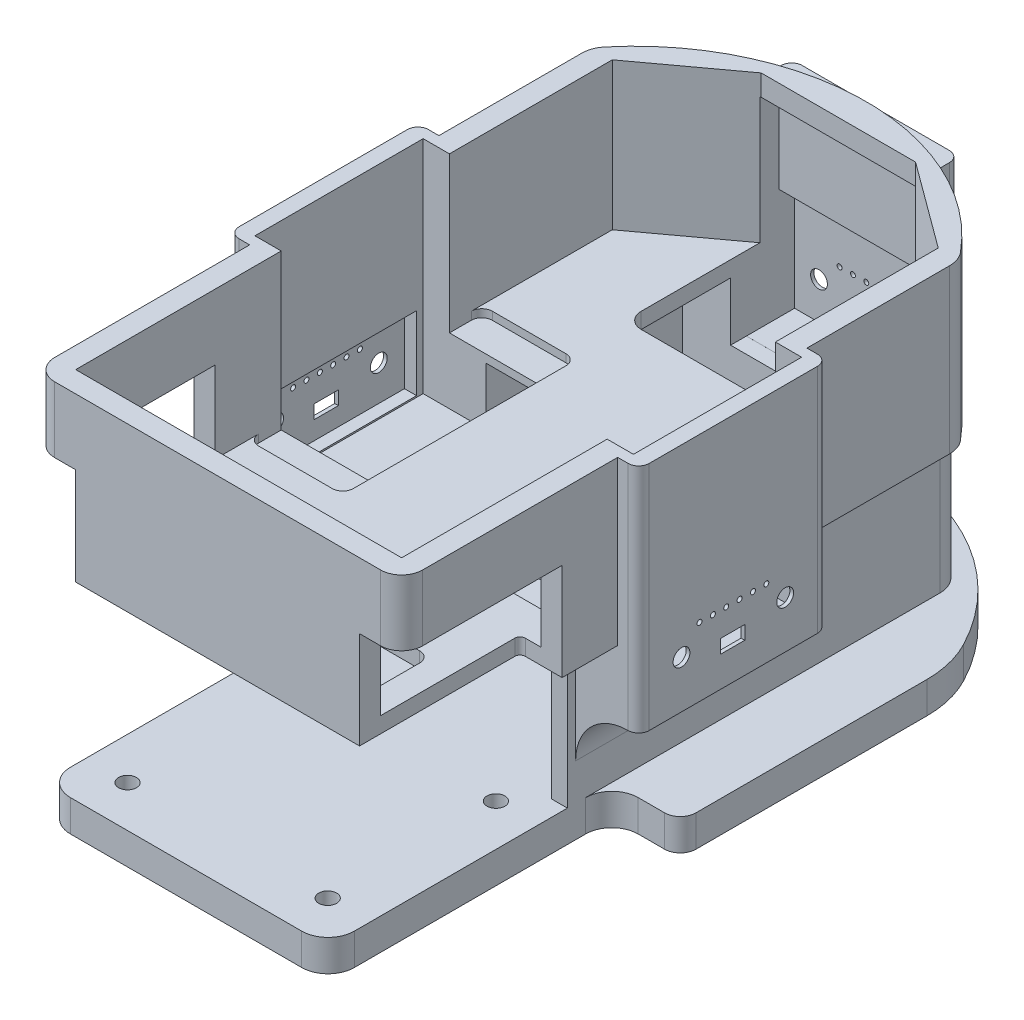
SolidWorks part; units mm, degrees
ref_plane "Plano frontal" through (0, 0, 0) normal (0, 0, 1) x (1, 0, 0)
ref_plane "Plano superior" through (0, 0, 0) normal (0, 1, 0) x (1, 0, 0)
ref_plane "Plano direito" through (0, 0, 0) normal (1, 0, 0) x (0, 0, -1)
sketch "Esboço4" plane through (0, 0, 0) normal (0, 1, 0) x (1, 0, 0)
  line L1 (-55, -54.8676) -> (25, -54.8676) construction
  line L2 (-55, -54.8676) -> (-55, 0.1324) construction
  line L3 (-55, 0.1324) -> (25, 0.1324) construction
  line L4 (25, -54.8676) -> (25, 0.1324) construction
  line L7 (-55, -98.8676) -> (25, -98.8676)
  line L8 (-55, -98.8676) -> (-55, 0.1324)
  line L10 (25, -98.8676) -> (25, 0.1324)
  line L11 (-15, 28.1324) -> (-15, -98.8676) construction
  arc A0 (-55, 0.1324) -> (25, 0.1324) centre (-15, -14.4391) cw
  point P0 (0, 0)
  dimension "D1" = 80
  dimension "D2" = 127
  dimension "D3" = 44
  dimension "D9" = 55
extrude "Ressalto-extrusão2" add sketch "Esboço4" against normal blind 6 contours L8 A0 L10 L7
sketch "Esboço5" plane through (0, 0, 0) normal (0, 1, 0) x (1, 0, 0)
  line L1 (9, -59.3376) -> (12, -59.3376)
  line L8 (-15, 28.1324) -> (-15, -110.1749) construction
  line L9 (12, -59.3376) -> (12, 16.5324)
  line L10 (12, 16.5324) -> (-42, 16.5324)
  line L11 (-42, 16.5324) -> (-42, -59.3376)
  line L12 (-42, -59.3376) -> (-39, -59.3376)
  line L13 (-39, -59.3376) -> (-39, 13.5324)
  line L14 (-39, 13.5324) -> (9, 13.5324)
  line L15 (9, 13.5324) -> (9, -59.3376)
  line L16 (-55, -98.8676) -> (25, -98.8676) construction
  line L18 (-55, -98.8676) -> (-55, 0.1324) construction
  arc A0 (25, 0.1324) -> (-55, 0.1324) centre (-15, -14.4391) ccw construction
  dimension "D1" = 3
  dimension "D2" = 3
  dimension "D3" = 115.4
  dimension "D4" = 3
  dimension "D5" = 48
  dimension "D6" = 13
  dimension "D7" = 75.87
extrude "Ressalto-extrusão3" add sketch "Esboço5" along normal blind 30
sketch "Esboço11" plane through (0, 30, 0) normal (0, 1, 0) x (1, 0, 0)
  line L3 (-50, 7.1324) -> (-15, 7.1324) construction
  line L7 (-15, -30.3676) -> (-15, -68.5788) construction
  line L13 (-42, -92.8676) -> (-42, -98.8676)
  line L14 (-42, -98.8676) -> (12, -98.8676)
  line L16 (12, -92.8676) -> (12, -98.8676)
  line L18 (-15, 28.1324) -> (-15, -108.0495) construction
  line L19 (-42, 16.5324) -> (-42, -59.3376) construction
  line L20 (-55, -98.8676) -> (25, -98.8676) construction
  line L21 (-50, 7.1324) -> (-50, -92.8676)
  line L22 (-42, -92.8676) -> (-50, -92.8676)
  line L23 (20, 7.1324) -> (20, -92.8676)
  line L24 (20, -92.8676) -> (12, -92.8676)
  line L25 (31.7419, -92.8676) -> (31.7419, 7.1324) construction
  line L26 (-15, -98.8676) -> (-15, 17.1324) construction
  arc A1 (25, 0.1324) -> (-55, 0.1324) centre (-15, -14.4391) ccw construction
  arc A2 (-50, 7.1324) -> (20, 7.1324) centre (-15, -19.5241) cw
  dimension "D1" = 68.5
  dimension "D2" = 100
  dimension "D3" = 116
  dimension "D4" = 35
  dimension "D5" = 6
extrude "Ressalto-extrusão4" add sketch "Esboço11" along normal blind 3
sketch "Esboço15" plane through (0, 33, 0) normal (0, 1, 0) x (1, 0, 0)
  line L9 (-46, -68.3394) -> (-50, 7.1324) construction
  line L11 (-50, 7.1324) -> (-50, -92.8676) construction
  line L13 (-46, 7.1998) -> (-46, -68.3394)
  line L14 (-50, -68.3394) -> (-50, 7.1324)
  line L15 (-50, -68.3394) -> (-46, -68.3394)
  line L16 (-15, 24.471) -> (-15, -143.5394) construction
  line L21 (19.0465, -92.8676) -> (19.0465, -75.5476) construction
  line L23 (-46, 7.1998) -> (16, 7.1998)
  line L26 (20, 7.1324) -> (20, -68.3394)
  line L27 (20, -92.8676) -> (20, 7.1324) construction
  line L29 (16, 7.1998) -> (16, -68.3394)
  line L30 (16, -68.3394) -> (20, -68.3394)
  arc A0 (20, 7.1324) -> (-50, 7.1324) centre (-15, -19.5241) ccw construction
  arc A1 (-50, 7.1324) -> (20, 7.1324) centre (-15, -19.5241) cw
  dimension "D1" = 17.32
  dimension "D2" = 4
extrude "Ressalto-extrusão7" add sketch "Esboço15" along normal blind 28
fillet "Filete1" radius 20 1 edges at (-55, -3, -0.1324)
fillet "Filete2" radius 20 1 edges at (25, -3, -0.1324)
sketch "Esboço22" plane through (0, 33, 0) normal (0, 1, 0) x (1, 0, 0)
  line L0 (-42, -94.8676) -> (12, -94.8676)
  line L1 (12, -94.8676) -> (12, -98.8676)
  line L2 (12, -98.8676) -> (-42, -98.8676)
  line L3 (-42, -98.8676) -> (-42, -94.8676)
  dimension "D1" = 4
extrude "Ressalto-extrusão8" add sketch "Esboço22" along normal blind 28
sketch "Esboço24" plane through (0, 0, 0) normal (0, 1, 0) x (1, 0, 0)
  line L0 (-55, -98.8676) -> (-55, -50.8676)
  line L1 (-55, -98.8676) -> (-55, -3.9763) construction
  line L2 (-55, -50.8676) -> (-42, -50.8676)
  line L3 (-42, -50.8676) -> (-42, -98.8676)
  line L4 (-55, -98.8676) -> (25, -98.8676) construction
  line L5 (-42, -98.8676) -> (-55, -98.8676)
  line L6 (-15, -98.8676) -> (-15, 24.4013) construction
  line L7 (12, -50.8676) -> (12, -98.8676)
  line L8 (25, -50.8676) -> (12, -50.8676)
  line L9 (25, -98.8676) -> (25, -50.8676)
  line L10 (12, -98.8676) -> (25, -98.8676)
  line L11 (-42, 16.5324) -> (-42, -59.3376) construction
  dimension "D2" = 48
extrude "Corte-extrusão5" cut sketch "Esboço24" against normal blind 6
fillet "Filete12" radius 5 1 edges at (-42, -3, 50.8676)
fillet "Filete13" radius 3 1 edges at (-55, -3, 50.8676)
fillet "Filete14" radius 5 1 edges at (12, -3, 50.8676)
fillet "Filete15" radius 3 1 edges at (25, -3, 50.8676)
ref_plane "Plano3" through (-15, 0, 0) normal (-1, 0, 0) x (0, 0, 1)
sketch "Esboço57" plane through (0, -6, 0) normal (0, -1, 0) x (-1, 0, 0)
  line L0 (15, -15.4) -> (15, 15.4) construction
  line L1 (35.5, -34.8676) -> (-5.5, -34.8676)
  line L2 (35.5, -34.8676) -> (35.5, 6.1324)
  line L3 (35.5, 6.1324) -> (-5.5, 6.1324)
  line L4 (-5.5, -34.8676) -> (-5.5, 6.1324)
  line L5 (35.5, -34.8676) -> (-5.5, 6.1324) construction
  line L6 (35.5, 6.1324) -> (-5.5, -34.8676) construction
  line L7 (15, 28.1324) -> (-35.47, 28.1324) construction
  line L9 (-17, -50.8676) -> (-35.47, -50.8676) construction
  line L10 (-35.47, -50.8676) -> (-35.47, 28.1324) construction
  arc A0 (52.7215, 5.2945) -> (-22.7215, 5.2945) centre (15, -14.4391) ccw construction
  point P0 (15, -14.3676)
  point P10 (15, 28.1324)
  point P11 (15, 6.1324)
  dimension "D1" = 41
  dimension "D2" = 41
  dimension "D3" = 36.5
  dimension "D4" = 79
extrude "Ressalto-extrusão10" add sketch "Esboço57" along normal blind 2
fillet "Filete23" radius 5 2 edges at (-42, 15, -16.5324) (12, 15, -16.5324)
sketch "Esboço58" plane through (0, 0, -7.1998) normal (0, 0, 1) x (1, 0, 0)
  line L0 (-29, 33) -> (-29, 46)
  line L1 (-46, 33) -> (16, 33) construction
  line L2 (-29, 46) -> (-1, 46)
  line L3 (-1, 46) -> (-1, 33)
  line L4 (-1, 33) -> (-29, 33)
  line L5 (-15, 16.225) -> (-15, -16.225) construction
  point P4 (-15, 46)
  dimension "D1" = 28
  dimension "D2" = 13
sketch "Esboço49" plane through (0, 33, 0) normal (0, 1, 0) x (1, 0, 0)
  line L0 (-46, 7.1998) -> (16, 7.1998) construction
  line L2 (-31, 26.3298) -> (1, 26.3298)
  line L3 (1, 26.3298) -> (1, 19.217)
  line L4 (1, 19.217) -> (-31, 19.217)
  line L5 (-31, 19.217) -> (-31, 26.3298)
  arc A2 (22.7215, 5.2945) -> (-52.7215, 5.2945) centre (-15, -14.4391) ccw construction
  point P13 (-15, 28.1324)
  point P14 (-15, 26.3298)
  dimension "D2" = 7.1127
  dimension "D3" = 19.13
  dimension "28" = 32
extrude "Ressalto-extrusão11" add sketch "Esboço49" along normal blind 26 and the other way blind 16.09
sketch "Esboço59" plane through (0, 33, 0) normal (0, 1, 0) x (1, 0, 0)
  line L0 (-50, -68.3394) -> (-50, -92.8676)
  line L1 (-50, -92.8676) -> (-42, -92.8676)
  line L2 (-42, -92.8676) -> (-42, -68.3394)
  line L3 (-42, -68.3394) -> (-50, -68.3394)
  line L4 (-15, 16.225) -> (-15, -16.225) construction
  line L5 (12, -92.8676) -> (12, -68.3394)
  line L6 (20, -92.8676) -> (12, -92.8676)
  line L7 (20, -68.3394) -> (20, -92.8676)
  line L8 (12, -68.3394) -> (20, -68.3394)
extrude "Corte-extrusão11" cut sketch "Esboço59" against normal blind 3
fillet "Filete27" radius 1 1 edges at (12, 31.5, 68.3394)
fillet "Filete28" radius 1 1 edges at (-42, 31.5, 68.3394)
fillet "Filete30" radius 5 1 edges at (20, 45.5, -7.1324)
fillet "Filete31" radius 5 1 edges at (-50, 45.5, -7.1324)
sketch "Esboço61" plane through (0, 61, 0) normal (0, 1, 0) x (1, 0, 0)
  line L2 (20, -68.3394) -> (20, -98.8676)
  line L3 (20, -98.8676) -> (12, -98.8676)
  line L4 (16, -68.3394) -> (20, -68.3394) construction
  line L9 (16, -68.3394) -> (16, -94.8676)
  line L10 (16, -94.8676) -> (12, -94.8676)
  line L11 (12, -94.8676) -> (12, -98.8676)
  line L12 (16, -68.3394) -> (20, -68.3394)
  line L13 (-15, 16.225) -> (-15, -16.225) construction
  line L14 (-46, -68.3394) -> (-46, -94.8676)
  line L15 (-46, -94.8676) -> (-42, -94.8676)
  line L16 (-42, -94.8676) -> (-42, -98.8676)
  line L17 (-50, -98.8676) -> (-42, -98.8676)
  line L18 (-50, -68.3394) -> (-50, -98.8676)
  line L19 (-46, -68.3394) -> (-50, -68.3394)
extrude "Ressalto-extrusão13" add sketch "Esboço61" against normal blind 12.5
fillet "Filete36" radius 4 1 edges at (20, 54.75, 98.8676)
fillet "Filete37" radius 4 1 edges at (-50, 54.75, 98.8676)
sketch "Esboço78" plane through (20, 0, 0) normal (1, 0, 0) x (0, 0, -1)
  line L0 (-57.7758, 61) -> (-21.7758, 61)
  line L1 (-21.7758, 61) -> (-21.7758, 17)
  line L3 (-57.7758, 61) -> (-57.7758, 17)
  line L4 (-57.7758, 17) -> (-21.7758, 17)
  line L5 (-55.8676, -6) -> (-98.8676, -6) construction
  line L7 (-94.8676, 61) -> (5.3881, 61) construction
  dimension "D1" = 41.0918
  dimension "D2" = 36
  dimension "D3" = 23
sketch "Esboço62" plane through (20, 0, 0) normal (1, 0, 0) x (0, 0, -1)
  line L0 (-47.7744, 31.6917) -> (-31.7744, 31.6917) construction
  line L1 (-47.7744, 20.8917) -> (-31.7744, 20.8917) construction
  line L3 (-47.7744, 31.6917) -> (-47.7744, 29.0817) construction
  line L4 (-31.7744, 31.6917) -> (-31.7744, 29.0817) construction
  line L5 (-31.7744, 29.0817) -> (-29.5544, 29.0741) construction
  line L6 (-29.5544, 23.5017) -> (-31.7744, 23.5017) construction
  line L7 (-31.7744, 23.5017) -> (-31.7744, 20.8917) construction
  line L9 (-47.7744, 23.5017) -> (-47.7744, 20.8917) construction
  line L10 (-54.5208, 19.2917) -> (-25.028, 19.2917)
  line L11 (-39.7744, 31.6917) -> (-39.7744, 20.8917) construction
  line L12 (-49.9944, 23.5017) -> (-47.7744, 23.5017) construction
  line L13 (-47.7744, 29.0817) -> (-49.9944, 29.0741) construction
  line L14 (-52.9208, 26.2879) -> (-52.9208, 1.5479) construction
  line L15 (-54.5208, 19.2917) -> (-54.5208, 33.2917)
  line L16 (-54.5208, 33.2917) -> (-25.028, 33.2917)
  line L17 (-25.028, 33.2917) -> (-25.028, 19.2917)
  line L19 (-94.8676, 61) -> (5.3881, 61) construction
  line L21 (-29.5544, 23.4984) -> (-50.1313, 23.4984) construction
  line L23 (-29.5544, 23.4984) -> (-51.8384, 23.4984) construction
  line L24 (-23.5489, 24.0817) -> (-9.8723, 24.0817) construction
  arc A0 (-29.5544, 29.0741) -> (-29.5544, 23.5017) centre (-29.4176, 26.2879) cw construction
  arc A2 (-49.9944, 29.0741) -> (-49.9944, 23.5017) centre (-50.1313, 26.2879) ccw construction
  point P16 (-52.9208, 26.2879)
  point P24 (-26.628, 26.2879)
  dimension "D2" = 2.7895
  dimension "D16" = 7.0038
  dimension "D3" = 16
  dimension "D4" = 2.61
  dimension "D5" = 27.7083
  dimension "D6" = 44.3468
  dimension "D7" = 2.61
  dimension "D8" = 1.6
  dimension "D9" = 5.58
  dimension "D10" = 1.6
  dimension "D11" = 2.22
  dimension "D12" = 2.22
  dimension "D13" = 10.8
  dimension "D14" = 9.21
  dimension "D15" = 5.5724
  dimension "D17" = 14
sketch "Esboço63" plane through (20, 0, 0) normal (1, 0, 0) x (0, 0, -1)
  line L0 (-39.7744, 31.6917) -> (-39.7744, 20.8917) construction
  line L1 (-47.7744, 31.6917) -> (-31.7744, 31.6917) construction
  line L2 (-47.7744, 20.8917) -> (-31.7744, 20.8917) construction
  line L3 (-47.7744, 31.6917) -> (-47.7744, 29.0817) construction
  line L4 (-42.1959, 25.3817) -> (-37.5959, 25.3817)
  line L5 (-37.5959, 25.3817) -> (-37.5959, 22.7817)
  line L6 (-42.1959, 25.3817) -> (-42.1959, 22.7817)
  line L7 (-42.1959, 22.7817) -> (-37.5959, 22.7817)
  circle A0 centre (-49.634, 25.9879) radius 1.6
  circle A2 centre (-29.9149, 25.9879) radius 1.6
  circle A3 centre (-46.2044, 30.0217) radius 0.475
  circle A4 centre (-43.6644, 30.0217) radius 0.475
  circle A5 centre (-41.1244, 30.0217) radius 0.475
  circle A6 centre (-38.5844, 30.0217) radius 0.475
  circle A7 centre (-36.0444, 30.0217) radius 0.475
  circle A8 centre (-33.5044, 30.0217) radius 0.475
  arc A11 (-29.5544, 23.5017) -> (-29.5544, 29.0741) centre (-29.4176, 26.2879) ccw construction
  point P5 (-26.628, 26.2879)
  dimension "D3" = 3.2
  dimension "D4" = 0.95
  dimension "D2" = 0.3
  dimension "D5" = 1.67
  dimension "D6" = 1.57
  dimension "D8" = 1.89
  dimension "D9" = 2.6
  dimension "D10" = 4.6
  dimension "D11" = 5.5785
  dimension "D12" = 3.2868
  dimension "D7" = 6
sketch "Esboço64" plane through (0, 0, -26.3298) normal (0, 0, -1) x (-1, 0, 0)
  line L0 (7, 45.4) -> (23, 45.4) construction
  line L1 (7, 34.6001) -> (23, 34.6001) construction
  line L2 (4.78, 37.21) -> (7, 37.21) construction
  line L3 (7, 45.4) -> (7, 42.786) construction
  line L4 (23, 45.4) -> (23, 42.0958) construction
  line L5 (23, 42.0958) -> (25.22, 42.0958) construction
  line L6 (25.22, 36.5169) -> (23, 36.5169) construction
  line L7 (23, 36.5169) -> (23, 34.6001) construction
  line L8 (7, 42.786) -> (4.78, 42.7775) construction
  line L9 (7, 37.21) -> (7, 34.6001) construction
  line L10 (-1, 59) -> (31, 59) construction
  line L11 (15, 46) -> (15, 27.7334) construction
  line L12 (-1, 16.91) -> (31, 16.91) construction
  line L13 (0.315, 18.91) -> (29.8252, 18.91)
  line L14 (0.315, 18.91) -> (0.315, 57.0001)
  line L15 (0.315, 57.0001) -> (29.8252, 57.0001)
  line L16 (29.8252, 57.0001) -> (29.8252, 18.91)
  arc A0 (25.22, 42.0958) -> (25.22, 36.5169) centre (25.2456, 39.3064) cw construction
  arc A1 (4.78, 42.7775) -> (4.78, 37.21) centre (4.6002, 39.9937) ccw construction
  dimension "D6" = 2.7895
  dimension "D7" = 2.7895
  dimension "D1" = 16
  dimension "D2" = 2.22
  dimension "D3" = 2.22
  dimension "D4" = 2.22
  dimension "D5" = 2.22
  dimension "D8" = 1.9999
  dimension "D9" = 29.5102
  dimension "D10" = 2
sketch "Esboço66" plane through (0, 0, -26.3298) normal (0, 0, -1) x (-1, 0, 0)
  line L0 (12.5785, 25.3801) -> (17.1785, 25.3801)
  line L1 (17.1785, 25.3801) -> (17.1785, 22.7801)
  line L2 (12.5785, 25.3801) -> (12.5785, 22.7801)
  line L3 (12.5785, 22.7801) -> (17.1785, 22.7801)
  line L5 (17.1785, 37.7901) -> (17.1785, 24.0801) construction
  line L6 (15, 27.7334) -> (15, 44.5612) construction
  line L7 (15, -16.225) -> (15, 16.225) construction
  line L8 (-1, 16.91) -> (-1, 59) construction
  line L9 (12.5785, 24.0801) -> (17.1785, 24.0801) construction
  circle A0 centre (4.8222, 25.9863) radius 1.6
  circle A2 centre (8.57, 30.0201) radius 0.475
  arc A3 (4.78, 42.7775) -> (4.78, 37.21) centre (4.6002, 39.9937) ccw construction
  circle A4 centre (25.1778, 25.9863) radius 1.6
  circle A5 centre (11.11, 30.0201) radius 0.475
  circle A6 centre (13.65, 30.0201) radius 0.475
  circle A7 centre (16.19, 30.0201) radius 0.475
  circle A8 centre (18.73, 30.0201) radius 0.475
  circle A9 centre (21.27, 30.0201) radius 0.475
  point P13 (1.8107, 39.9938)
  dimension "D2" = 3.0116
  dimension "D3" = 1.57
  dimension "D4" = 4.0338
  dimension "D6" = 13.71
  dimension "D7" = 5.5785
  dimension "D8" = 2.6
  dimension "D9" = 4.6
  dimension "D11" = 18.1785
  dimension "D12" = 3.2062
  dimension "D5" = 6
extrude "Corte-extrusão15" cut sketch "Esboço66" against normal blind 1
extrude "Corte-extrusão17" cut sketch "Esboço64" along normal blind 15.5 from surface at -19.13 starting at face at (-15, 47, -7.1998)
fillet "Filete49" radius 2 1 edges at (1, 37.955, -26.3298)
fillet "Filete52" radius 2 1 edges at (-31, 37.955, -26.3298)
sketch "Esboço73" plane through (0, 0, 98.8676) normal (0, 0, 1) x (1, 0, 0)
  line L0 (-42, 0) -> (12, 0)
  line L1 (12, 0) -> (12, -6)
  line L2 (12, -6) -> (-42, -6)
  line L3 (-42, -6) -> (-42, 0)
extrude "Ressalto-extrusão14" add sketch "Esboço73" along normal blind 6
fillet "Filete60" radius 5 1 edges at (12, -3, 104.8676)
fillet "Filete61" radius 5 1 edges at (-42, -3, 104.8676)
sketch "Esboço77" plane through (0, -6, 0) normal (0, -1, 0) x (-1, 0, 0)
  line L0 (-12, -96.9676) -> (-4.04, -96.9676) construction
  line L1 (-12, -55.8676) -> (-12, -99.8676) construction
  line L2 (37, -104.8676) -> (-7, -104.8676) construction
  line L3 (15, -104.8676) -> (15, -101.5371) construction
  line L4 (-4.04, -96.9676) -> (-4.04, -64.9676) construction
  circle A0 centre (-4.04, -96.9676) radius 1.7
  circle A1 centre (-4.04, -64.9676) radius 1.7
  circle A2 centre (34.04, -64.9676) radius 1.7
  circle A3 centre (34.04, -96.9676) radius 1.7
  dimension "D2" = 3.4
  dimension "D5" = 3.4
  dimension "D1" = 7.96
  dimension "D3" = 7.9
  dimension "D4" = 32
extrude "Corte-extrusão25" cut sketch "Esboço77" against normal blind 6
extrude "Ressalto-extrusão16" add sketch "Esboço78" along normal blind 4
sketch "Esboço81" plane through (24, 0, 0) normal (1, 0, 0) x (0, 0, -1)
  line L0 (-57.7758, 30) -> (-21.7758, 30)
  line L1 (-21.7758, 17) -> (-21.7758, 61) construction
  line L2 (-59.3376, 30) -> (11.5324, 30) construction
  line L3 (-21.7758, 30) -> (-21.7758, 17)
  line L4 (-57.7758, 17) -> (-21.7758, 17) construction
  line L5 (-21.7758, 17) -> (-57.7758, 17)
  line L6 (-57.7758, 61) -> (-57.7758, 17) construction
  line L7 (-57.7758, 17) -> (-57.7758, 30)
  line L8 (-21.7758, 61) -> (-57.7758, 61) construction
  dimension "D1" = 31
  dimension "D2" = 13
  dimension "D3" = 36
extrude "Ressalto-extrusão17" add sketch "Esboço81" against normal blind 8 from surface at -4 starting at face at (20, 23.5, 39.7758)
extrude "Corte-extrusão29" cut sketch "Esboço62" along normal blind 3.3
extrude "Corte-extrusão30" cut sketch "Esboço63" along normal blind 4
sketch "Esboço83" plane through (0, 61, 0) normal (0, 1, 0) x (1, 0, 0)
  line L0 (21, -23.7758) -> (21, -55.7758)
  line L1 (24, -21.7758) -> (20, -21.7758) construction
  line L2 (24, -57.7758) -> (20, -57.7758) construction
  line L3 (21, -23.7758) -> (-2, -23.7758)
  line L5 (-2, -23.7758) -> (-2, -55.7758)
  line L7 (-2, -55.7758) -> (21, -55.7758)
  line L8 (24, -21.7758) -> (24, -57.7758) construction
  dimension "D1" = 2
  dimension "D2" = 2
  dimension "D3" = 3
  dimension "D4" = 23
extrude "Corte-extrusão31" cut sketch "Esboço83" against normal blind 42
sketch "Esboço86" plane through (24, 0, 0) normal (1, 0, 0) x (0, 0, -1)
  line L5 (-47.7744, 35.2062) -> (-31.8209, 35.2062)
  line L7 (-47.7744, 35.2062) -> (-47.7744, 28.5721)
  line L10 (-47.7744, 28.5721) -> (-31.8209, 28.5721)
  line L11 (-31.8209, 28.5721) -> (-31.8209, 35.2062)
  line L12 (-47.7744, 29.0817) -> (-49.9944, 29.0741) construction
  line L13 (-59.3376, 0) -> (-99.8676, 0) construction
  dimension "D1" = 0.5097
  dimension "D2" = 15.9536
  dimension "D3" = 6.6342
  dimension "D4" = 28.5721
mirror "Espelhar7" about plane through (-15, 0, 0) normal (-1, 0, 0) of "Ressalto-extrusão16"
sketch "Esboço92" plane through (-54, 0, 0) normal (-1, 0, 0) x (0, 0, 1)
  line L0 (21.7758, 30) -> (57.7758, 30)
  line L1 (57.7758, 30) -> (57.7758, 17)
  line L2 (-16.5324, 0) -> (-16.5324, 30) construction
  line L4 (57.7758, 17) -> (21.7758, 17)
  line L6 (21.7758, 17) -> (21.7758, 30)
  line L7 (21.7758, 61) -> (57.7758, 61) construction
  dimension "D1" = 36
  dimension "D2" = 13
  dimension "D3" = 31
  dimension "D4" = 38.3082
extrude "Ressalto-extrusão18" add sketch "Esboço92" against normal blind 8 from surface at -4 starting at face at (-50, 23.5, 39.7758)
mirror "Espelhar21" about plane through (-15, 0, 0) normal (-1, 0, 0) of "Corte-extrusão31", "Corte-extrusão30", "Corte-extrusão29"
sketch "Esboço93" plane through (-54, 0, 0) normal (-1, 0, 0) x (0, 0, 1)
  line L0 (30.7758, 35.2062) -> (30.7758, 28.5721)
  line L1 (30.7758, 28.5721) -> (48.7758, 28.5721)
  line L2 (48.7758, 28.5721) -> (48.7758, 35.2062)
  line L3 (48.7758, 35.2062) -> (30.7758, 35.2062)
  line L5 (3.9763, 0) -> (-5.2945, 0) construction
  line L6 (39.7758, 61) -> (39.7758, 11.0081) construction
  line L7 (21.7758, 61) -> (57.7758, 61) construction
  point P6 (39.7758, 35.2062)
  dimension "D1" = 18
  dimension "D2" = 6.6342
  dimension "D3" = 28.5721
fillet "Filete67" radius 2 2 edges at (24, 39, 57.7758) (24, 39, 21.7758)
fillet "Filete68" radius 2 2 edges at (-54, 39, 57.7758) (-54, 39, 21.7758)
sketch "Esboço96" plane through (0, 33, 0) normal (0, 1, 0) x (1, 0, 0)
  line L0 (-37.0473, -80.4776) -> (7.0473, -80.4776)
  line L1 (7.0473, -80.4776) -> (7.0473, -93.5976)
  line L2 (-37.0473, -80.4776) -> (-37.0473, -93.5976)
  line L3 (-37.0473, -93.5976) -> (7.0473, -93.5976)
  line L4 (-15, -94.8676) -> (-15, -59.2914) construction
  line L5 (16, -94.8676) -> (-46, -94.8676) construction
  line L6 (12, -94.8676) -> (-42, -94.8676) construction
  point P8 (-15, -80.4776)
  dimension "D1" = 44.0945
  dimension "D2" = 1.27
  dimension "D3" = 13.12
extrude "Corte-extrusão34" cut sketch "Esboço96" against normal blind 3
sketch "Esboço98" plane through (0, 18.91, 0) normal (0, 1, 0) x (1, 0, 0)
  line L0 (-29.8252, 19.1998) -> (-29.8252, 7.1998)
  line L1 (-29.8252, 7.1998) -> (-0.315, 7.1998)
  line L2 (-0.315, 22.6998) -> (-0.315, 19.217) construction
  line L3 (-0.315, 7.1998) -> (-29.8252, 7.1998) construction
  line L4 (-0.315, 7.1998) -> (-0.315, 19.1998)
  line L5 (-0.315, 19.1998) -> (-29.8252, 19.1998)
  dimension "D1" = 12
extrude "Corte-extrusão37" cut sketch "Esboço98" along normal blind 28
fillet "Filete69" radius 10 3 edges at (12, 17, 39.7758) (17, 17, 57.7758) (17, 17, 21.7758)
fillet "Filete70" radius 10 3 edges at (-42, 17, 39.7758) (-47, 17, 57.7758) (-47, 17, 21.7758)
fillet "Filete77" radius 2 4 edges at (7.0473, 31.5, 80.4776) (7.0473, 31.5, 93.5976) (-37.0473, 31.5, 80.4776) (-37.0473, 31.5, 93.5976)
sketch "Esboço107" plane through (0, 33, 0) normal (0, 1, 0) x (1, 0, 0)
  line L0 (16, -55.7758) -> (16, -62.0576)
  line L1 (16, -55.7758) -> (16, -68.3394) construction
  line L2 (16, -62.0576) -> (-2, -55.7758) construction
  line L3 (-2, -55.7758) -> (-2, -62.0576)
  line L4 (-2, -62.0576) -> (16, -62.0576)
  line L5 (-2, -55.7758) -> (16, -55.7758)
  line L6 (-2, -23.7758) -> (-2, -17.6187)
  line L7 (-2, -17.6187) -> (16, -17.6187)
  line L8 (16, 7.1998) -> (16, -23.7758) construction
  line L9 (16, -23.7758) -> (16, -17.6187)
  line L10 (-2, -23.7758) -> (16, -23.7758)
  line L11 (-15, 16.225) -> (-15, -16.225) construction
  line L12 (-28, -55.7758) -> (-28, -62.0576)
  line L13 (-28, -62.0576) -> (-46, -62.0576)
  line L14 (-46, -55.7758) -> (-46, -62.0576)
  line L15 (-28, -55.7758) -> (-46, -55.7758)
  line L16 (-28, -23.7758) -> (-28, -17.6187)
  line L17 (-28, -17.6187) -> (-46, -17.6187)
  line L18 (-46, -23.7758) -> (-46, -17.6187)
  line L19 (-28, -23.7758) -> (-46, -23.7758)
extrude "Corte-extrusão45" cut sketch "Esboço107" against normal blind 1.5
fillet "Filete83" radius 2 8 edges at (-28, 32.25, 62.0576) (16, 32.25, 62.0576) (-2, 32.25, 62.0576) (-46, 32.25, 62.0576) (-28, 32.25, 17.6187) (16, 32.25, 17.6187) (-2, 32.25, 17.6187) (-46, 32.25, 17.6187)
sketch "Esboço113" plane through (0, 61, 0) normal (0, 1, 0) x (1, 0, 0)
  line L0 (-0.315, 19.1998) -> (16, 7.1998)
  line L1 (16, 7.1998) -> (-0.315, 7.1998)
  line L2 (-0.315, 7.1998) -> (-0.315, 19.1998)
  line L3 (-15, 16.225) -> (-15, -16.225) construction
  line L4 (-46, 7.1998) -> (-29.685, 7.1998)
  line L5 (-29.685, 19.1998) -> (-46, 7.1998)
  line L6 (-29.685, 7.1998) -> (-29.685, 19.1998)
  arc A0 (18.8466, 8.5823) -> (-48.8466, 8.5823) centre (-15, -19.5241) ccw construction
  dimension "D1" = 38.7239
  dimension "D2" = 20.2529
extrude "Corte-extrusão46" cut sketch "Esboço113" against normal blind 28
sketch "Esboço115" plane through (0, 0, -19.217) normal (0, 0, 1) x (1, 0, 0)
  line L0 (1, 16.91) -> (1, 30)
  line L1 (1, 30) -> (-31, 30)
  line L2 (-31, 30) -> (-31, 16.91)
  line L3 (-31, 16.91) -> (1, 16.91)
extrude "Ressalto-extrusão20" add sketch "Esboço115" along normal blind 2.68
sketch "Esboço116" plane through (0, 61, 0) normal (0, 1, 0) x (1, 0, 0)
  line L0 (-29.685, 19.1998) -> (-0.315, 19.1998)
  line L1 (-29.685, 7.1998) -> (-29.685, 19.1998) construction
  line L2 (-0.315, 19.1998) -> (-0.315, 7.1998)
  line L3 (-0.315, 7.1998) -> (-29.8252, 7.1998)
  line L4 (-29.8252, 7.1998) -> (-29.685, 19.1998)
extrude "Corte-extrusão47" cut sketch "Esboço116" against normal blind 4 contours L3 L4 L0 L2
sketch "Esboço119" plane through (0, 30, 0) normal (0, 1, 0) x (1, 0, 0)
  line L0 (-29.8252, 16.537) -> (-29.8252, 19.217)
  line L1 (-29.8252, 19.217) -> (-0.315, 19.217)
  line L2 (-0.315, 19.217) -> (-0.315, 16.537)
  line L3 (-0.315, 16.537) -> (-29.8252, 16.537)
extrude "Corte-extrusão48" cut sketch "Esboço119" against normal blind 11.09 contours L0 L1 L2 L3
sketch "Esboço120" plane through (0, 0, -22.6998) normal (0, 0, 1) x (1, 0, 0)
  line L0 (-29.8252, 18.91) -> (-29.8252, 32.91)
  line L1 (-29.8252, 18.91) -> (-29.8252, 57.0001) construction
  line L2 (-29.8252, 32.91) -> (-0.315, 32.91)
  line L3 (-0.315, 57.0001) -> (-0.315, 18.91) construction
  line L4 (-0.315, 32.91) -> (-0.315, 18.91)
  line L5 (-0.315, 18.91) -> (-29.8252, 18.91)
  dimension "D1" = 14
extrude "Corte-extrusão49" cut sketch "Esboço120" against normal blind 3
sketch "Esboço121" plane through (0, 0, -22.6998) normal (0, 0, 1) x (1, 0, 0)
  line L0 (-29.8252, 32.91) -> (-29.8252, 40.02)
  line L1 (-29.8252, 32.91) -> (-29.8252, 57.0001) construction
  line L2 (-29.8252, 40.02) -> (-0.315, 40.02)
  line L3 (-0.315, 57.0001) -> (-0.315, 32.91) construction
  line L4 (-0.315, 40.02) -> (-29.8252, 32.91) construction
  line L5 (-0.315, 32.91) -> (-0.315, 40.02)
  line L6 (-29.8252, 32.91) -> (-0.315, 32.91)
extrude "Corte-extrusão50" cut sketch "Esboço121" against normal blind 3
sketch "Esboço122" plane through (0, 33, 0) normal (0, 1, 0) x (1, 0, 0)
  line L0 (-29.8252, 13.5324) -> (-29.8252, -6.4676)
  line L1 (-29.8252, -6.4676) -> (0, -6.4676)
  line L2 (0, -6.4676) -> (-0.315, 13.1998)
  line L3 (-0.315, 19.1998) -> (-0.315, 7.1998) construction
  line L4 (-0.315, 13.1998) -> (-29.8252, 13.5324)
  dimension "D1" = 20
extrude "Corte-extrusão51" cut sketch "Esboço122" against normal blind 3
fillet "Filete88" radius 3 2 edges at (0, 31.5, 6.4676) (-29.8252, 31.5, 6.4676)
fillet "Filete89" radius 3 1 edges at (-15.0701, 57.0001, -22.6998)
